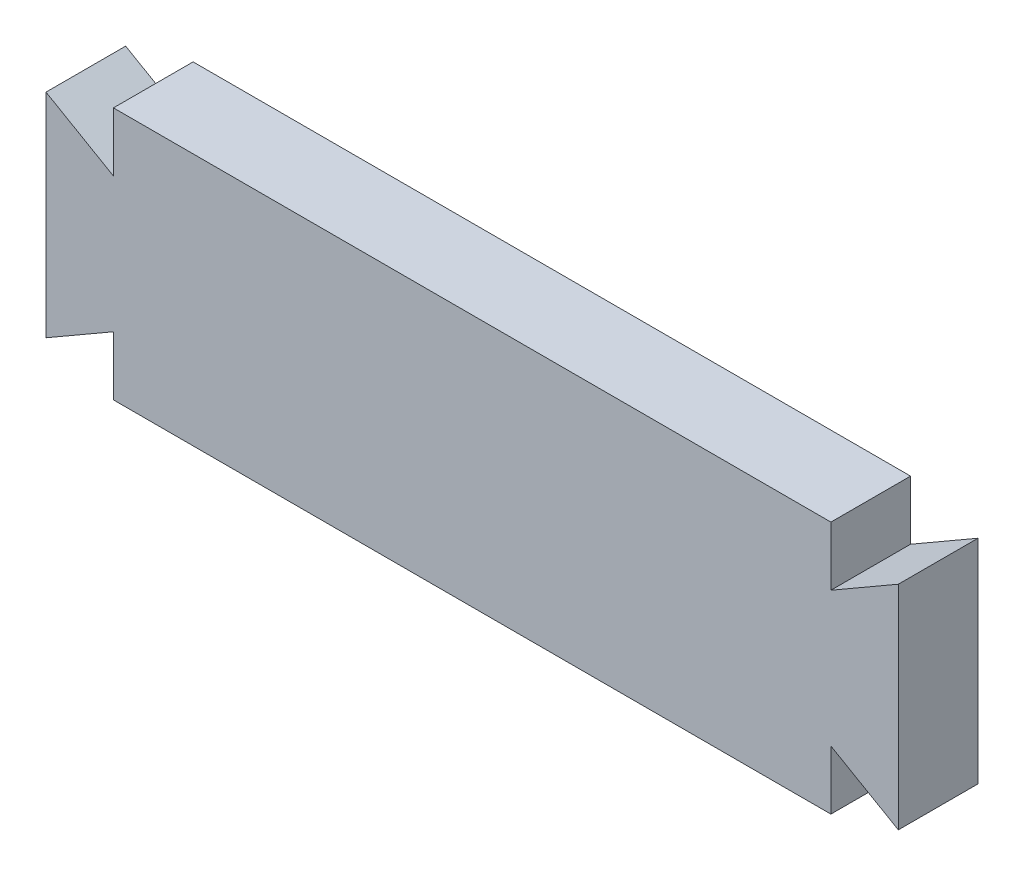
SolidWorks part; units mm, degrees
ref_plane "Front Plane" through (0, 0, 0) normal (0, 0, 1) x (1, 0, 0)
ref_plane "Top Plane" through (0, 0, 0) normal (0, 1, 0) x (1, 0, 0)
ref_plane "Right Plane" through (0, 0, 0) normal (1, 0, 0) x (0, 0, -1)
sketch "Sketch1" plane through (0, 0, 0) normal (0, 0, 1) x (1, 0, 0)
  line L0 (-17.55, 0) -> (17.55, 0) construction
  line L1 (-16.05, -4.0065) -> (-16.05, 4.0065)
  line L2 (-16.05, -4.0065) -> (-19.05, -4.0065) construction
  line L3 (-16.05, -4.0065) -> (-16.05, 4.0065) construction
  line L4 (-16.05, 4.0065) -> (-19.05, 4.0065) construction
  line L5 (-19.05, -4.0065) -> (-19.05, 4.0065) construction
  line L6 (-16.05, -4.0065) -> (-19.05, 4.0065) construction
  line L7 (-16.05, 4.0065) -> (-19.05, -4.0065) construction
  line L8 (16.05, -4.0065) -> (19.05, -4.0065) construction
  line L9 (16.05, -4.0065) -> (16.05, 4.0065) construction
  line L10 (16.05, 4.0065) -> (19.05, 4.0065) construction
  line L11 (19.05, -4.0065) -> (19.05, 4.0065) construction
  line L12 (16.05, -4.0065) -> (19.05, 4.0065) construction
  line L13 (16.05, 4.0065) -> (19.05, -4.0065) construction
  line L14 (-16.05, 4.0065) -> (-13.51, 4.0065) construction
  line L15 (-16.05, 4.0065) -> (-16.05, -4.0065) construction
  line L16 (-16.05, -4.0065) -> (-13.51, -4.0065) construction
  line L17 (-13.51, 4.0065) -> (-13.51, -4.0065) construction
  line L18 (16.05, -4.0065) -> (13.51, -4.0065) construction
  line L19 (16.05, -4.0065) -> (16.05, 4.0065) construction
  line L20 (16.05, 4.0065) -> (13.51, 4.0065) construction
  line L21 (13.51, -4.0065) -> (13.51, 4.0065) construction
  line L22 (-16.05, 4.0065) -> (-13.51, 2.54)
  line L23 (-13.51, 2.54) -> (-13.51, 4.7625)
  line L24 (-13.51, 4.7625) -> (13.51, 4.7625)
  line L25 (13.51, 4.7625) -> (13.51, 2.54)
  line L26 (13.51, 2.54) -> (16.05, 4.0065)
  line L27 (16.05, 4.0065) -> (16.05, -4.0065)
  line L33 (-16.05, -4.0065) -> (-13.51, -2.54)
  line L34 (-13.51, -2.54) -> (-13.51, -4.7625)
  line L35 (-13.51, -4.7625) -> (13.51, -4.7625)
  line L36 (13.51, -4.7625) -> (13.51, -2.54)
  line L37 (13.51, -2.54) -> (16.05, -4.0065)
  line L38 (0, -4.7625) -> (0, 4.7625) construction
  dimension "D2" = 3
  dimension "D3" = 2.54
  dimension "D4" = 60
  dimension "D5" = 5.08
  dimension "D6" = 9.525
  dimension "D1" = 38.1
extrude "Boss-Extrude1" add sketch "Sketch1" along normal mid plane 3
equation "\"StageWidth\" = 1.5in"
equation "\"PlateThickness\"= 3mm"
equation "\"D2@Sketch1\"=\"PlateThickness\""
equation "\"CapThickness\"= .1in"
equation "\"D3@Sketch1\"=\"CapThickness\""
equation "\"DoveTailAngle\"= 60"
equation "\"D4@Sketch1\"=\"DoveTailAngle\""
equation "\"DoveTailWidth\"= .2in"
equation "\"D5@Sketch1\"=\"DoveTailWidth\""
equation "\"ConnectorWidth\"= .375in"
equation "\"D6@Sketch1\"=\"ConnectorWidth\""
equation "\"D1@Boss-Extrude1\"=\"PlateThickness\""
equation "\"D1@Sketch1\"=\"StageWidth\""
